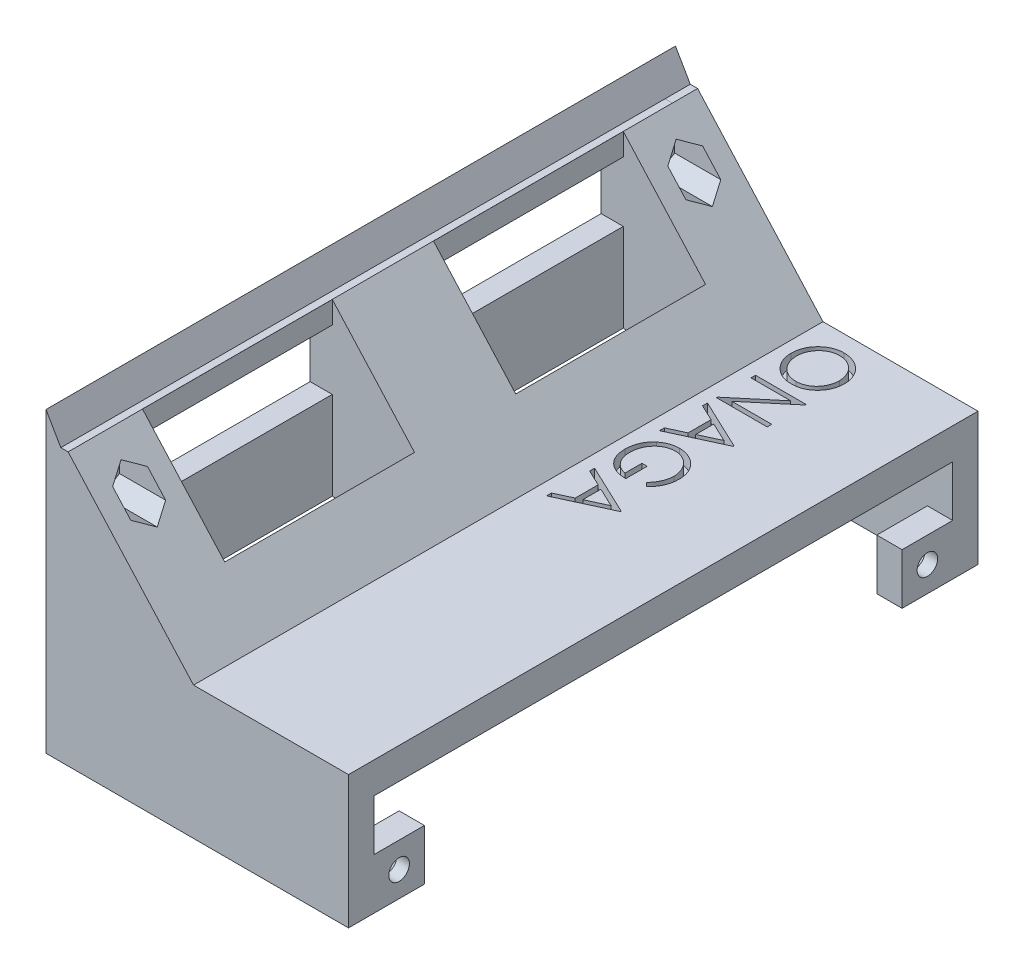
SolidWorks part; units mm, degrees
ref_plane "Alzado" through (0, 0, 0) normal (0, 0, 1) x (1, 0, 0)
ref_plane "Planta" through (0, 0, 0) normal (0, 1, 0) x (1, 0, 0)
ref_plane "Vista lateral" through (0, 0, 0) normal (1, 0, 0) x (0, 0, -1)
sketch "Croquis1" plane through (0, 0, 0) normal (0, 0, 1) x (1, 0, 0)
  line L3 (-2, 100) -> (32.2611, 100) construction
  line L5 (2, 89.0656) -> (2, 42)
  line L6 (2, 42) -> (49.8187, 42)
  line L9 (2, 89.0656) -> (4.3416, 85.0068)
  line L10 (4.3416, 85.0068) -> (5.4971, 85.0068)
  line L12 (49.8187, 57.9939) -> (49.8187, 42)
  line L13 (5.4971, 85.0068) -> (25.3169, 62.9939)
  line L14 (49.8187, 57.9939) -> (49.8187, 62.9939)
  line L15 (49.8187, 62.9939) -> (25.3169, 62.9939)
  dimension "D1" = 2
  dimension "D2" = 4.3416
  dimension "D3" = 5.4971
  dimension "D4" = 25.3169
  dimension "D5" = 49.8187
  dimension "D6" = 42
  dimension "D7" = 57.9939
  dimension "D8" = 85.0068
  dimension "D9" = 89.0656
  dimension "D10" = 100
  dimension "D11" = 62.9939
extrude "Saliente-Extruir3" add sketch "Croquis1" against normal blind 4
sketch "Croquis4" plane through (0, 0, -4) normal (0, 0, -1) x (-1, 0, 0)
  line L0 (-5.4971, 85.0068) -> (-4.3416, 85.0068)
  line L1 (-4.3416, 85.0068) -> (-2, 89.0656)
  line L2 (-2, 89.0656) -> (-2, 58.0656)
  line L3 (-2, 89.0656) -> (-2, 42) construction
  line L4 (-2, 58.0656) -> (-5.5, 58.0656)
  line L6 (-5.5, 58.0656) -> (-5.5, 85.0036)
  line L7 (-5.4971, 85.0068) -> (-5.5, 85.0036)
  line L9 (-2, 42) -> (-49.8187, 42) construction
  dimension "D1" = 3.5
  dimension "D2" = 16.0656
  dimension "D3" = 43.0036
extrude "Saliente-Extruir5" add sketch "Croquis4" along normal blind 91.5
sketch "Croquis5" plane through (0, 0, -95.5) normal (0, 0, -1) x (-1, 0, 0)
  line L0 (-49.8187, 42) -> (-49.8187, 62.9939)
  line L1 (-49.8187, 62.9939) -> (-25.3169, 62.9939)
  line L2 (-25.3169, 62.9939) -> (-5.5, 85.0036)
  line L3 (-5.5, 85.0036) -> (-4.3416, 85.0068)
  line L4 (-4.3416, 85.0068) -> (-2, 89.0656)
  line L5 (-2, 89.0656) -> (-2, 42)
  line L6 (-2, 42) -> (-49.8187, 42)
extrude "Saliente-Extruir6" add sketch "Croquis5" along normal blind 4
sketch "Croquis6" plane through (0, 0, -4) normal (0, 0, -1) x (-1, 0, 0)
  line L0 (-5.5, 85.0036) -> (-25.3169, 62.9939)
  line L1 (-25.3169, 62.9939) -> (-49.8187, 62.9939)
  line L5 (-5.5, 58.0656) -> (-5.5, 85.0036)
  line L6 (-5.5, 85.0036) -> (-5.5, 58.0656) construction
  line L8 (-49.8187, 62.9939) -> (-49.8187, 58.0656)
  line L9 (-49.8187, 58.0656) -> (-5.5, 58.0656)
extrude "Saliente-Extruir7" add sketch "Croquis6" along normal up to vertex (7.75 mm away)
sketch "Croquis7" plane through (0, 0, -95.5) normal (0, 0, 1) x (1, 0, 0)
  line L0 (5.4971, 85.0068) -> (25.3169, 62.9939)
  line L1 (25.3169, 62.9939) -> (49.8187, 62.9939)
  line L5 (5.5, 58.0656) -> (5.4971, 85.0068)
  line L8 (49.8187, 62.9939) -> (49.8187, 58.0656)
  line L9 (49.8187, 58.0656) -> (5.5, 58.0656)
extrude "Saliente-Extruir8" add sketch "Croquis7" along normal up to vertex (7.75 mm away)
sketch "Croquis8" plane through (0, 0, -87.75) normal (0, 0, 1) x (1, 0, 0)
  line L0 (5.5, 85.0036) -> (5.5, 58.0656) construction
  line L1 (18.5, 58.0656) -> (18.5, 70.5651)
  line L2 (25.3169, 62.9939) -> (5.5, 85.0036) construction
  line L3 (18.5, 70.5651) -> (25.3169, 62.9939)
  line L4 (25.3169, 62.9939) -> (49.8187, 62.9939)
  line L5 (49.8187, 62.9939) -> (49.8187, 58.0656)
  line L6 (49.8187, 58.0656) -> (18.5, 58.0656)
  line L7 (5.5, 58.0656) -> (49.8187, 58.0656) construction
  dimension "D1" = 13
extrude "Saliente-Extruir9" add sketch "Croquis8" along normal up to vertex (76 mm away)
sketch "Croquis9" plane through (18.5, 0, 0) normal (-1, 0, 0) x (0, 0, 1)
  line L10 (-87.75, 70.5651) -> (-87.75, 58.0656) construction
  line L11 (-57.75, 58.0656) -> (-41.75, 58.0656)
  line L12 (-57.75, 58.0656) -> (-57.75, 69.9995)
  line L13 (-57.75, 69.9995) -> (-41.75, 69.9995)
  line L14 (-41.75, 58.0656) -> (-41.75, 69.9995)
  line L15 (-11.75, 58.0656) -> (-87.75, 58.0656) construction
  dimension "D1" = 30
  dimension "D2" = 46
  dimension "D3" = 11.9339
extrude "Saliente-Extruir10" add sketch "Croquis9" along normal up to vertex (13 mm away)
sketch "Croquis12" plane through (0, 69.9995, 0) normal (0, 1, 0) x (1, 0, 0)
  line L1 (18.5, 57.75) -> (5.5, 57.75)
  line L2 (18.5, 57.75) -> (18.5, 41.75)
  line L3 (18.5, 41.75) -> (5.5, 41.75)
  line L4 (5.5, 57.75) -> (5.5, 41.75)
extrude "Saliente-Extruir12" add sketch "Croquis12" along normal up to vertex (15.0074 mm away)
sketch "Croquis13" plane through (0, 0, -87.75) normal (0, 0, 1) x (1, 0, 0)
  line L0 (5.4971, 85.0068) -> (18.5, 70.5651)
  line L1 (18.5, 70.5651) -> (18.5, 85.0068)
  line L2 (18.5, 85.0068) -> (5.4971, 85.0068)
extrude "Cortar-Extruir2" cut sketch "Croquis13" along normal up to vertex
sketch "Croquis14" plane through (0, 58.0656, 0) normal (0, -1, 0) x (1, 0, 0)
  line L0 (5.5, -41.75) -> (2, -41.75) construction
  line L1 (2, -95.5) -> (2, -4) construction
  line L2 (2, -41.75) -> (2, -57.75) construction
  line L3 (5.5, -57.75) -> (2, -57.75) construction
  line L4 (2, -49.75) -> (2, -43.75)
  line L5 (2, -49.75) -> (2, -55.75)
  line L6 (2, -43.75) -> (8, -43.75)
  line L7 (2, -55.75) -> (8, -55.75)
  line L8 (8, -55.75) -> (8, -43.75)
  dimension "D1" = 6
extrude "Cortar-Extruir3" cut sketch "Croquis14" against normal blind 22
sketch "Croquis15" plane through (0, 0, -43.75) normal (0, 0, -1) x (-1, 0, 0)
  line L0 (-8, 80.0656) -> (-2, 80.0656)
  line L1 (-2, 80.0656) -> (-2, 86.7145)
  line L2 (-2, 86.7145) -> (-8, 80.0656)
  line L5 (-2, 42) -> (-2, 89.0656) construction
  line L6 (-2, 80.0656) -> (-2, 58.0656) construction
  line L7 (-8, 58.0656) -> (-2, 58.0656) construction
  dimension "D1" = 6
  dimension "D2" = 22
  dimension "D3" = 28.6489
extrude "Cortar-Extruir4" cut sketch "Croquis15" along normal up to vertex (12 mm away) up to point (2, 80.0656, -55.75)
sketch "Croquis18" plane through (2, 0, 0) normal (-1, 0, 0) x (0, 0, 1)
  line L0 (-99.5, 79.0656) -> (-87.75, 79.0656) construction
  line L1 (-99.5, 42) -> (-99.5, 89.0656) construction
  line L2 (-93.625, 79.0656) -> (-93.625, 89.0656) construction
  line L3 (-99.5, 89.0656) -> (0, 89.0656) construction
  line L4 (0, 79.0656) -> (-11.75, 79.0656) construction
  line L5 (-93.625, 75.8856) -> (-90.871, 77.4756)
  line L6 (-90.871, 77.4756) -> (-90.871, 80.6556)
  line L7 (-90.871, 80.6556) -> (-93.625, 82.2456)
  line L8 (-93.625, 82.2456) -> (-96.379, 80.6556)
  line L9 (-96.379, 80.6556) -> (-96.379, 77.4756)
  line L10 (-96.379, 77.4756) -> (-93.625, 75.8856)
  line L11 (0, 89.0656) -> (0, 42) construction
  line L12 (-5.875, 79.0656) -> (-5.875, 89.0656) construction
  line L14 (-5.875, 82.2456) -> (-8.629, 80.6556)
  line L15 (-8.629, 80.6556) -> (-8.629, 77.4756)
  line L16 (-8.629, 77.4756) -> (-5.875, 75.8856)
  line L17 (-5.875, 75.8856) -> (-3.121, 77.4756)
  line L18 (-3.121, 77.4756) -> (-3.121, 80.6556)
  line L19 (-3.121, 80.6556) -> (-5.875, 82.2456)
  circle A1 centre (-93.625, 79.0656) radius 2.754 construction
  circle A3 centre (-5.875, 79.0656) radius 2.754 construction
  dimension "D1" = 5.5079
extrude "Cortar-Extruir5" cut sketch "Croquis18" against normal blind 12
sketch "Croquis19" plane through (2, 0, 0) normal (-1, 0, 0) x (0, 0, 1)
  line L0 (-93.625, 82.2456) -> (-93.625, 75.8856) construction
  line L1 (-90.871, 77.4756) -> (-90.871, 80.6556) construction
  line L2 (-5.875, 75.8856) -> (-5.875, 82.2456) construction
  line L4 (-93.625, 75.8856) -> (-90.871, 77.4756)
  line L5 (-90.871, 77.4756) -> (-90.871, 80.6556)
  line L6 (-90.871, 80.6556) -> (-93.625, 82.2456)
  line L7 (-93.625, 82.2456) -> (-96.379, 80.6556)
  line L8 (-96.379, 80.6556) -> (-96.379, 77.4756)
  line L9 (-96.379, 77.4756) -> (-93.625, 75.8856)
  line L10 (-5.875, 75.8856) -> (-3.121, 77.4756)
  line L11 (-3.121, 77.4756) -> (-3.121, 80.6556)
  line L12 (-3.121, 80.6556) -> (-5.875, 82.2456)
  line L13 (-5.875, 82.2456) -> (-8.629, 80.6556)
  line L14 (-8.629, 80.6556) -> (-8.629, 77.4756)
  line L15 (-8.629, 77.4756) -> (-5.875, 75.8856)
  circle A0 centre (-5.875, 79.0656) radius 1.625
  circle A1 centre (-93.625, 79.0656) radius 1.625
  dimension "D1" = 3.25
  dimension "D2" = 82.2421
extrude "Saliente-Extruir13" add sketch "Croquis19" against normal blind 3
sketch "Croquis20" plane through (5.5, 0, 0) normal (1, 0, 0) x (0, 0, -1)
  line L0 (41.75, 85.0036) -> (41.75, 70.5651) construction
  line L5 (87.75, 70.5651) -> (87.75, 85.0036) construction
  line L10 (43.75, 58.0656) -> (43.75, 58.6312) construction
  line L11 (87.75, 72.0036) -> (57.75, 72.0036)
  line L12 (87.75, 72.0036) -> (87.75, 81.5036)
  line L13 (87.75, 81.5036) -> (57.75, 81.5036)
  line L14 (57.75, 72.0036) -> (57.75, 81.5036)
  line L15 (41.75, 72.0036) -> (11.75, 72.0036)
  line L16 (41.75, 72.0036) -> (41.75, 81.5036)
  line L17 (41.75, 81.5036) -> (11.75, 81.5036)
  line L18 (11.75, 72.0036) -> (11.75, 81.5036)
  line L19 (43.75, 58.0656) -> (11.75, 58.0656) construction
  dimension "D1" = 14
  dimension "D2" = 13.938
  dimension "D3" = 23.438
extrude "Cortar-Extruir6" cut sketch "Croquis20" against normal up to vertex (3.5 mm away) up to point (2, 42, 0)
sketch "Croquis23" plane through (0, 58.0656, 0) normal (0, -1, 0) x (1, 0, 0)
  line L0 (7.7, -11.75) -> (7.7, -4) construction
  line L1 (18.5, -11.75) -> (5.5, -11.75) construction
  line L2 (7.7, -11.85) -> (7.7, -8) construction
  line L3 (2, -4) -> (49.8187, -4) construction
  line L4 (15.2, -8) -> (15.2, -11.75) construction
  line L5 (15.2, -11.75) -> (7.7, -11.75)
  line L6 (15.2, -11.75) -> (15.2, -4)
  line L7 (15.2, -4) -> (7.7, -4)
  line L8 (7.7, -11.75) -> (7.7, -4)
  line L9 (5.5, -41.75) -> (18.5, -41.75) construction
  line L10 (15.2, -41.75) -> (8, -41.75)
  line L11 (15.2, -41.75) -> (15.2, -57.75)
  line L12 (15.2, -57.75) -> (8, -57.75)
  line L13 (8, -41.75) -> (8, -57.75)
  line L14 (15.2, -41.15) -> (15.2, -45) construction
  line L15 (5.5, -57.75) -> (18.5, -57.75) construction
  line L16 (7.7, -91.5) -> (7.7, -95.5) construction
  line L17 (49.8187, -95.5) -> (2, -95.5) construction
  line L18 (5.5, -87.75) -> (18.5, -87.75) construction
  line L19 (7.7, -95.5) -> (15.2, -95.5)
  line L20 (7.7, -95.5) -> (7.7, -87.75)
  line L21 (7.7, -87.75) -> (15.2, -87.75)
  line L22 (15.2, -95.5) -> (15.2, -87.75)
  line L23 (15.2, -87.65) -> (15.2, -91.5) construction
  line L24 (18.5, -11.75) -> (18.5, -41.75) construction
  dimension "D1" = 10.5
extrude "Saliente-Extruir14" add sketch "Croquis23" along normal up to vertex (6.576 mm away)
sketch "Croquis24" plane through (15.2, 0, 0) normal (1, 0, 0) x (0, 0, -1)
  line L0 (8.9794, 52.469) -> (8, 51.4896)
  line L1 (8, 51.4896) -> (11.75, 55.2396) construction
  line L2 (8, 51.4896) -> (8, 49.4896) construction
  line L3 (8, 51.4896) -> (11.75, 51.4896)
  line L4 (11.75, 51.4896) -> (11.75, 55.2396)
  line L5 (11.75, 51.4896) -> (11.75, 58.0656) construction
  line L6 (11.75, 55.2396) -> (8.9794, 52.469)
  line L7 (41.75, 51.4896) -> (41.75, 54.7396)
  line L8 (41.75, 51.4896) -> (41.75, 58.0656) construction
  line L9 (41.25, 55.2396) -> (45, 51.4896) construction
  line L10 (41.75, 54.7396) -> (45, 51.4896)
  line L11 (57.75, 51.4896) -> (41.75, 51.4896) construction
  line L12 (45, 51.4896) -> (45, 49.4896) construction
  line L13 (45, 51.4896) -> (41.75, 51.4896)
  line L14 (56.1873, 53.1768) -> (54.5, 51.4896)
  line L15 (54.5, 51.4896) -> (58.25, 55.2396) construction
  line L16 (54.5, 51.4896) -> (54.5, 49.4896) construction
  line L17 (54.5, 51.4896) -> (57.75, 51.4896)
  line L18 (57.75, 51.4896) -> (57.75, 54.7396)
  line L19 (57.75, 51.4896) -> (57.75, 58.0656) construction
  line L20 (57.75, 54.7396) -> (56.1873, 53.1768)
  line L21 (89.0314, 53.9582) -> (91.5, 51.4896)
  line L22 (87.75, 55.2396) -> (91.5, 51.4896) construction
  line L23 (95.5, 51.4896) -> (87.75, 51.4896) construction
  line L24 (91.5, 51.4896) -> (87.75, 51.4896)
  line L25 (87.75, 51.4896) -> (87.75, 55.2396)
  line L26 (87.75, 51.4896) -> (87.75, 58.0656) construction
  line L27 (87.75, 55.2396) -> (89.0314, 53.9582)
  dimension "D1" = 14.4373
  dimension "D2" = 47.2814
  dimension "D3" = 32.7706
extrude "Cortar-Extruir7" cut sketch "Croquis24" against normal up to vertex (7.2 mm away)
sketch "Croquis25" plane through (0, 51.4896, 0) normal (0, -1, 0) x (1, 0, 0)
  circle A0 centre (11.45, -54.5) radius 1.6
  circle A1 centre (11.45, -45) radius 1.6
  circle A2 centre (11.45, -8) radius 1.6
  circle A3 centre (11.45, -91.5) radius 1.6
  dimension "D1" = 3.2
extrude "Cortar-Extruir8" cut sketch "Croquis25" against normal blind 3
sketch "Croquis28" plane through (2, 0, 0) normal (-1, 0, 0) x (0, 0, 1)
  line L0 (-95.5, 50) -> (-87.5, 42) construction
  line L1 (-95.5, 42) -> (-87.5, 42)
  line L2 (-95.5, 42) -> (-95.5, 50)
  line L3 (-95.5, 50) -> (-87.5, 50)
  line L4 (-87.5, 42) -> (-87.5, 50)
  line L13 (-4, 42) -> (-12, 42)
  line L14 (-4, 42) -> (-4, 50)
  line L15 (-4, 50) -> (-12, 50)
  line L16 (-12, 42) -> (-12, 50)
  line L17 (-12, 50) -> (-4, 42) construction
  line L18 (-43.75, 86.7145) -> (-43.75, 58.0656) construction
  circle A0 centre (-91.5, 46) radius 1.625
  circle A1 centre (-8, 46) radius 1.625
  dimension "D1" = 3.25
  dimension "D2" = 31.75
extrude "Saliente-Extruir15" add sketch "Croquis28" against normal blind 3
sketch "Croquis29" plane through (5, 0, 0) normal (1, 0, 0) x (0, 0, -1)
  line L1 (11.17, 46) -> (9.585, 48.7453)
  line L2 (9.585, 48.7453) -> (6.415, 48.7453)
  line L3 (6.415, 48.7453) -> (4.83, 46)
  line L4 (4.83, 46) -> (6.415, 43.2547)
  line L5 (6.415, 43.2547) -> (9.585, 43.2547)
  line L6 (9.585, 43.2547) -> (11.17, 46)
  line L7 (94.68, 46) -> (93.09, 48.754)
  line L8 (93.09, 48.754) -> (89.91, 48.754)
  line L9 (89.91, 48.754) -> (88.32, 46)
  line L10 (88.32, 46) -> (89.91, 43.246)
  line L11 (89.91, 43.246) -> (93.09, 43.246)
  line L12 (93.09, 43.246) -> (94.68, 46)
  circle A0 centre (8, 46) radius 2.7453 construction
  circle A1 centre (91.5, 46) radius 2.754 construction
  dimension "D1" = 5.4906
  dimension "D2" = 5.5079
extrude "Cortar-Extruir9" cut sketch "Croquis29" against normal blind 2
sketch "Croquis30" plane through (5, 0, 0) normal (1, 0, 0) x (0, 0, -1)
  line L0 (12, 50) -> (12, 49)
  line L1 (12, 50) -> (12, 42) construction
  line L2 (12, 50) -> (11, 50)
  line L3 (4, 50) -> (12, 50) construction
  line L4 (11, 50) -> (12, 49)
  line L5 (87.5, 50) -> (87.5, 49)
  line L6 (87.5, 42) -> (87.5, 50) construction
  line L7 (87.5, 50) -> (88.5, 50)
  line L8 (87.5, 50) -> (95.5, 50) construction
  line L9 (88.5, 50) -> (87.5, 49)
  line L10 (6.415, 43.2547) -> (9.585, 43.2547) construction
  dimension "D1" = 5.7453
extrude "Cortar-Extruir10" cut sketch "Croquis30" against normal up to vertex
sketch "Croquis31" plane through (0, 62.9939, 0) normal (0, 1, 0) x (1, 0, 0)
  line L0 (27.3169, 97.5) -> (25.3169, 97.5) construction
  line L2 (25.3169, 99.5) -> (25.3169, 0) construction
  line L3 (27.3169, 99.5) -> (27.3169, 97.5) construction
  line L4 (25.3169, 99.5) -> (49.8187, 99.5) construction
  line L5 (27.3169, 97.5) -> (27.3169, 57.5) construction
  text T0 "ONAGA" font "Century Gothic" height 8
extrude "Cortar-Extruir11" cut sketch "Croquis31" against normal blind 2
sketch "Croquis33" plane through (49.8187, 0, 0) normal (1, 0, 0) x (0, 0, -1)
  line L0 (4, 42) -> (4, 58.0656) construction
  line L1 (4, 50.0328) -> (12, 50.0328)
  line L2 (4, 50.0328) -> (4, 42)
  line L3 (4, 42) -> (12, 42)
  line L4 (12, 50.0328) -> (12, 42)
  line L5 (95.5, 58.0656) -> (95.5, 42) construction
  line L6 (95.5, 50.0328) -> (87.5, 50.0328)
  line L7 (95.5, 50.0328) -> (95.5, 42)
  line L8 (95.5, 42) -> (87.5, 42)
  line L9 (87.5, 50.0328) -> (87.5, 42)
  line L10 (4, 42) -> (0, 42) construction
  circle A0 centre (91.5, 46) radius 1.625
  circle A1 centre (8, 46) radius 1.625
  dimension "D1" = 3.25
extrude "Saliente-Extruir17" add sketch "Croquis33" against normal blind 4
sketch "Croquis34" plane through (45.8187, 0, 0) normal (-1, 0, 0) x (0, 0, 1)
  line L1 (-88.33, 46) -> (-89.915, 48.7453)
  line L2 (-89.915, 48.7453) -> (-93.085, 48.7453)
  line L3 (-93.085, 48.7453) -> (-94.67, 46)
  line L4 (-94.67, 46) -> (-93.085, 43.2547)
  line L5 (-93.085, 43.2547) -> (-89.915, 43.2547)
  line L6 (-89.915, 43.2547) -> (-88.33, 46)
  line L7 (-11.17, 46) -> (-9.585, 43.2547)
  line L8 (-9.585, 43.2547) -> (-6.415, 43.2547)
  line L9 (-6.415, 43.2547) -> (-4.83, 46)
  line L10 (-4.83, 46) -> (-6.415, 48.7453)
  line L11 (-6.415, 48.7453) -> (-9.585, 48.7453)
  line L12 (-9.585, 48.7453) -> (-11.17, 46)
  circle A0 centre (-91.5, 46) radius 2.7453 construction
  circle A1 centre (-8, 46) radius 2.7453 construction
  dimension "D1" = 5.4906
extrude "Cortar-Extruir12" cut sketch "Croquis34" against normal blind 2
sketch "Croquis35" plane through (0, 58.0656, 0) normal (0, -1, 0) x (1, 0, 0)
  line L6 (18.5, -67.95) -> (26.5, -67.95) construction
  line L7 (18.5, -11.75) -> (18.5, -41.75) construction
  line L9 (17.95, -31.55) -> (23.85, -31.55) construction
  line L10 (26.5, -21.45) -> (18.5, -21.45)
  line L11 (26.5, -21.45) -> (26.5, -31.55)
  line L12 (26.5, -31.55) -> (18.5, -31.55)
  line L13 (18.5, -21.45) -> (18.5, -31.55)
  line L14 (18.5, -57.75) -> (18.5, -87.75) construction
  line L15 (23.85, -67.95) -> (17.95, -67.95) construction
  line L16 (15.2, -11.75) -> (15.2, -4) construction
  line L17 (26.5, -67.95) -> (18.5, -67.95)
  line L18 (26.5, -67.95) -> (26.5, -78.0641)
  line L19 (26.5, -78.0641) -> (18.5, -78.0641)
  line L20 (18.5, -67.95) -> (18.5, -78.0641)
  line L21 (49.8187, -4) -> (15.2, -4) construction
  dimension "D1" = 11.3
  dimension "D2" = 17.45
  dimension "D3" = 74.0641
extrude "Cortar-Extruir13" cut sketch "Croquis35" against normal blind 2
